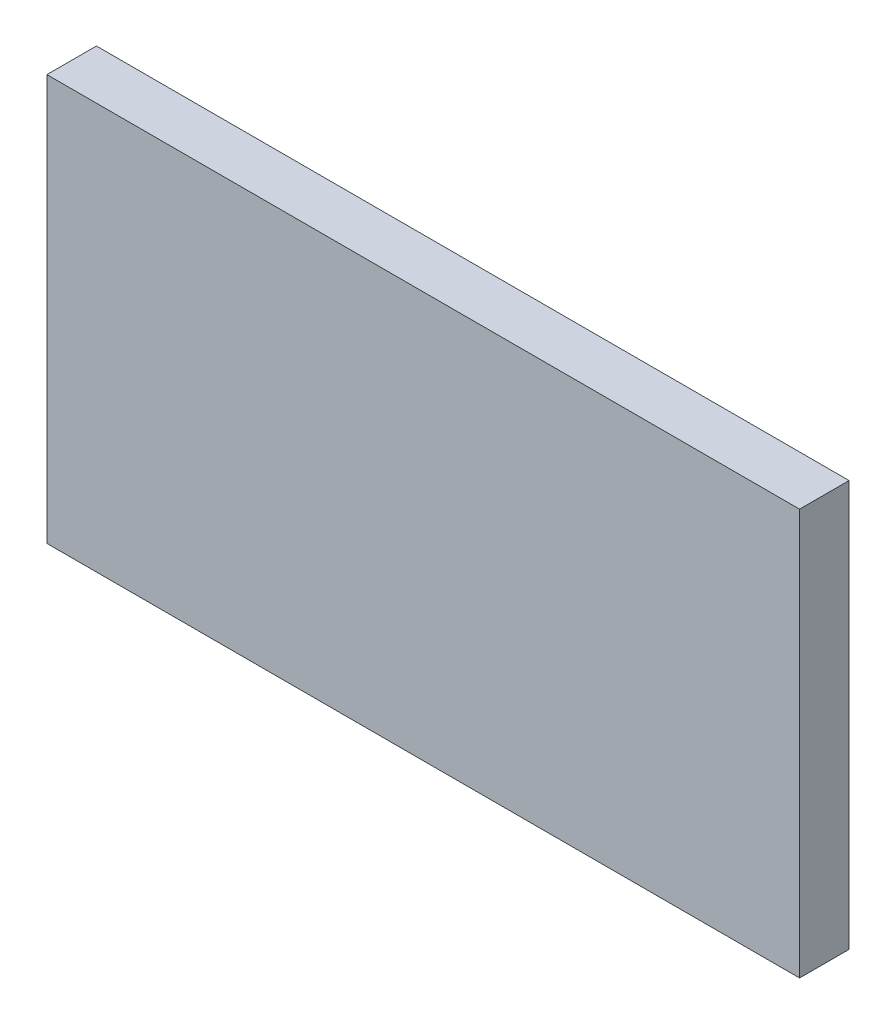
SolidWorks part; units mm, degrees
ref_plane "Plan de face" through (0, 0, 0) normal (0, 0, 1) x (1, 0, 0)
ref_plane "Plan de dessus" through (0, 0, 0) normal (0, 1, 0) x (1, 0, 0)
ref_plane "Plan de droite" through (0, 0, 0) normal (1, 0, 0) x (0, 0, -1)
sketch "Esquisse1" plane through (0, 0, 0) normal (0, 0, 1) x (1, 0, 0)
  line L1 (-152, -82) -> (152, -82)
  line L2 (-152, -82) -> (-152, 82)
  line L3 (-152, 82) -> (152, 82)
  line L4 (152, -82) -> (152, 82)
  line L5 (-152, -82) -> (152, 82) construction
  line L6 (-152, 82) -> (152, -82) construction
  point P0 (0, 0)
  dimension "D1" = 164
  dimension "D2" = 304
extrude "Boss.-Extru.1" add sketch "Esquisse1" along normal blind 20
